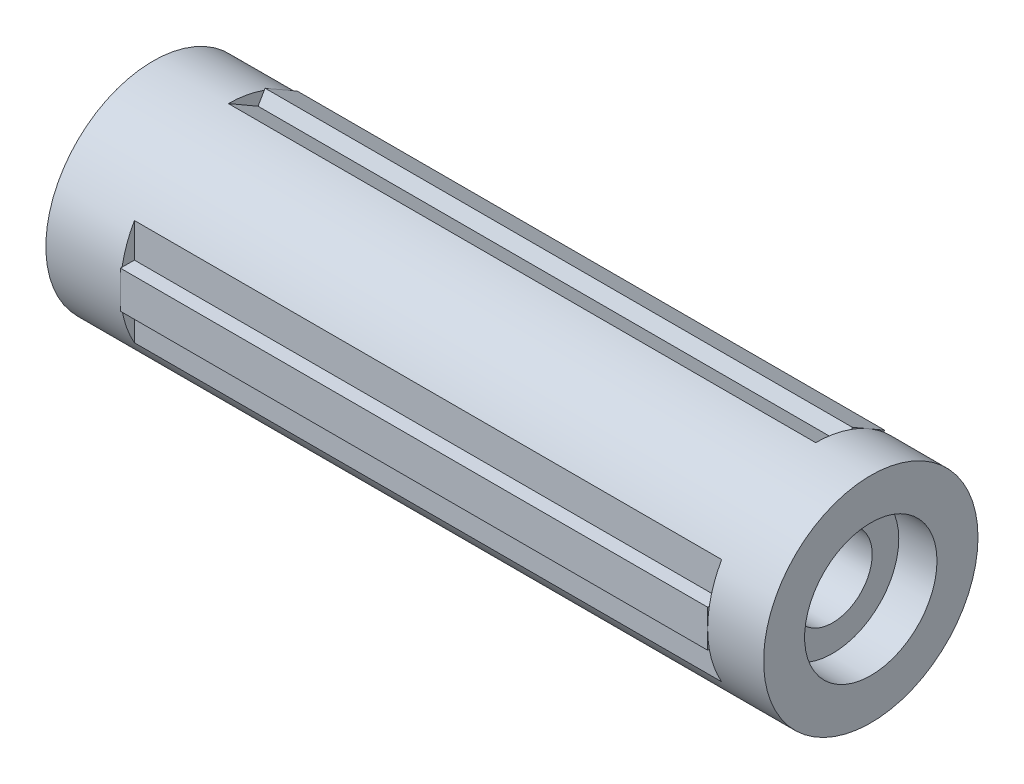
SolidWorks part; units mm, degrees
material "PVC hart"
ref_plane "Ebene vorne" through (0, 0, 0) normal (0, 0, 1) x (1, 0, 0)
ref_plane "Ebene oben" through (0, 0, 0) normal (0, 1, 0) x (1, 0, 0)
ref_plane "Ebene rechts" through (0, 0, 0) normal (1, 0, 0) x (0, 0, -1)
sketch "Skizze1" plane through (0, 0, 0) normal (1, 0, 0) x (0, 0, -1)
  circle A0 centre (0, 0) radius 11.5
  dimension "D1" = 23
extrude "Aufsatz-Linear austragen1" add sketch "Skizze1" along normal blind 77
sketch "Skizze2" plane through (77, 0, 0) normal (1, 0, 0) x (0, 0, -1)
  circle A0 centre (0, 0) radius 7.1
  dimension "D1" = 14.2
extrude "Schnitt-Linear austragen1" cut sketch "Skizze2" against normal blind 4.1
sketch "Skizze3" plane through (72.9, 0, 0) normal (1, 0, 0) x (0, 0, -1)
  circle A0 centre (0, 0) radius 4.25
  dimension "D1" = 8.5
extrude "Schnitt-Linear austragen2" cut sketch "Skizze3" against normal blind 43
sketch "Skizze4" plane through (0, 0, 0) normal (-1, 0, 0) x (0, 0, 1)
  circle A0 centre (0, 0) radius 9.6
  dimension "D1" = 19.2
extrude "Schnitt-Linear austragen3" cut sketch "Skizze4" against normal blind 12.75
sketch "Skizze7" plane through (77, 0, 0) normal (1, 0, 0) x (0, 0, -1)
  line L0 (0, 13.4409) -> (0, -14.2481) construction
  line L1 (-11.5, 7.5) -> (-10, 7.5)
  line L2 (-11.5, 7.5) -> (-11.5, -7.5)
  line L3 (-11.5, -7.5) -> (-10, -7.5)
  line L4 (-10, 7.5) -> (-10, -7.5)
  dimension "D1" = 1.5
  dimension "D2" = 15
  dimension "D3" = 10
extrude "Schnitt-Linear austragen4" cut sketch "Skizze7" against normal blind 63 from offset 6 offset against normal yes
sketch "Skizze8" plane through (0, 0, 10) normal (0, 0, 1) x (1, 0, 0)
  line L0 (71, -5.6789) -> (71, 5.6789) construction
  line L1 (8, 2) -> (71, 2)
  line L2 (8, 2) -> (8, -2)
  line L3 (8, -2) -> (71, -2)
  line L4 (71, 2) -> (71, -2)
  line L5 (8, 2) -> (71, -2) construction
  line L6 (8, -2) -> (71, 2) construction
  line L7 (12.65, 0) -> (-12.65, 0) construction
  point P0 (39.5, 0)
  dimension "D1" = 31.5
  dimension "D3" = 63
  dimension "D4" = 4
extrude "Aufsatz-Linear austragen2" add sketch "Skizze8" along normal blind 1.5
sketch "Skizze10" plane through (12.75, 0, 0) normal (-1, 0, 0) x (0, 0, 1)
  line L1 (4.0389, -2.2407) -> (3.96, 2.3774)
  line L2 (3.96, 2.3774) -> (-0.0789, 4.6181)
  line L3 (-0.0789, 4.6181) -> (-4.0389, 2.2407)
  line L4 (-4.0389, 2.2407) -> (-3.96, -2.3774)
  line L5 (-3.96, -2.3774) -> (0.0789, -4.6181)
  line L6 (0.0789, -4.6181) -> (4.0389, -2.2407)
  circle A0 centre (0, 0) radius 4 construction
  dimension "D1" = 8
extrude "Schnitt-Linear austragen6" cut sketch "Skizze10" against normal blind 13.5
sketch "Skizze12" plane through (26.25, 0, 0) normal (-1, 0, 0) x (0, 0, 1)
  circle A0 centre (0, 0) radius 3
  dimension "D1" = 6
extrude "Schnitt-Linear austragen7" cut sketch "Skizze12" against normal blind 2
pattern_circular "Kreismuster3" count 3 over 360 about axis through (0, 0, 0) along (1, 0, 0) of "Aufsatz-Linear austragen2", "Schnitt-Linear austragen4"
